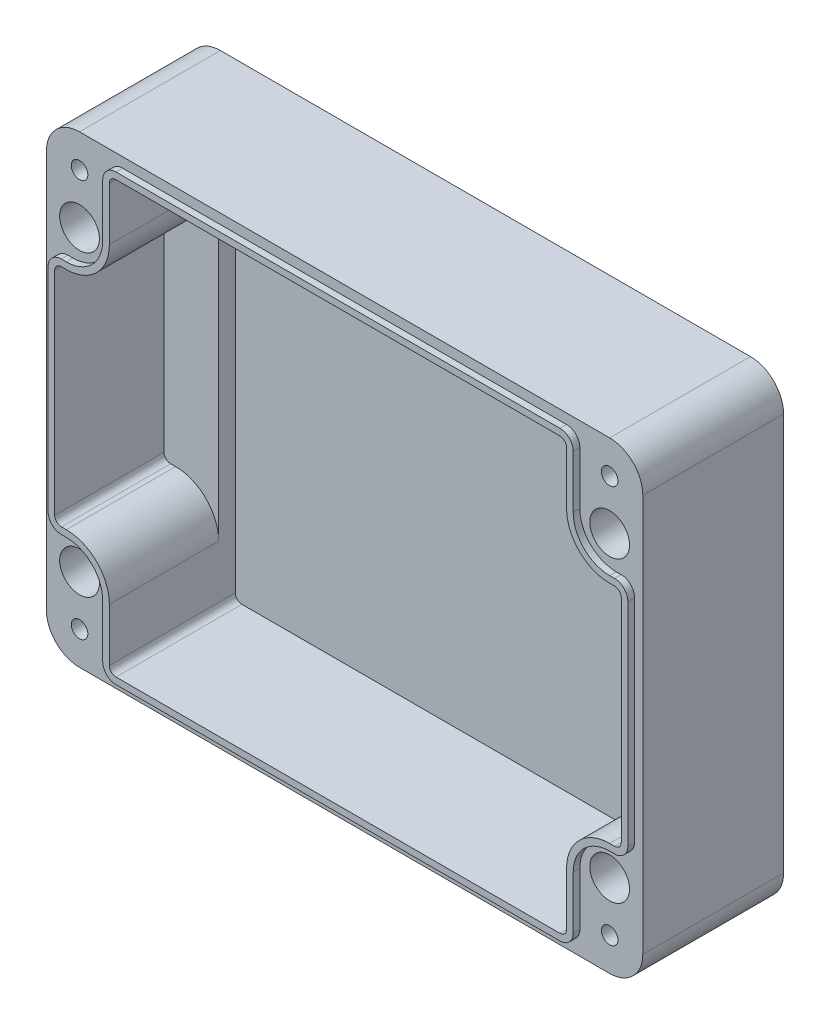
SolidWorks part; units mm, degrees
material "ألمنيوم خلائطي"
ref_plane "Front" through (0, 0, 0) normal (0, 0, 1) x (1, 0, 0)
ref_plane "Top" through (0, 0, 0) normal (0, 1, 0) x (1, 0, 0)
ref_plane "Right" through (0, 0, 0) normal (1, 0, 0) x (0, 0, -1)
sketch "Sketch1" plane through (0, 0, 0) normal (0, 0, 1) x (1, 0, 0)
  line L0 (90, 70) -> (-90, -70) construction
  line L1 (-90, 70) -> (90, 70)
  line L2 (-90, 70) -> (-90, -70)
  line L3 (-90, -70) -> (90, -70)
  line L4 (90, 70) -> (90, -70)
  dimension "D1" = 180
  dimension "D2" = 140
extrude "Boss-Extrude1" add sketch "Sketch1" along normal blind 42.5
sketch "Sketch2" plane through (0, 0, 42.5) normal (0, 0, 1) x (1, 0, 0)
  line L0 (-69, 65) -> (69, -65) construction
  line L1 (-69, 65) -> (69, 65)
  line L2 (-69, 65) -> (-69, 34)
  line L3 (-69, -65) -> (69, -65)
  line L4 (69, 65) -> (69, 34)
  line L5 (-85.5, 34) -> (-69, 34)
  line L6 (-85.5, 34) -> (-85.5, -34)
  line L7 (-85.5, -34) -> (-69, -34)
  line L8 (85.5, 34) -> (85.5, -34)
  line L9 (85.5, 34) -> (-85.5, -34) construction
  line L10 (69, 34) -> (85.5, 34)
  line L11 (69, -34) -> (85.5, -34)
  line L12 (69, -34) -> (69, -65)
  line L13 (-69, -34) -> (-69, -65)
  dimension "D1" = 130
  dimension "D2" = 138
  dimension "D3" = 171
  dimension "D4" = 68
extrude "Cut-Extrude1" cut sketch "Sketch2" against normal blind 36
fillet "Fillet1" radius 2 8 edges at (-69, -65, 24.5) (69, -65, 24.5) (69, 65, 24.5) (-69, 65, 24.5) (85.5, 34, 24.5) (85.5, -34, 24.5) (-85.5, -34, 24.5) (-85.5, 34, 24.5)
fillet "Fillet2" radius 13 4 edges at (69, 34, 24.5) (69, -34, 24.5) (-69, -34, 24.5) (-69, 34, 24.5)
fillet "Fillet3" radius 10 4 edges at (-90, -70, 21.25) (-90, 70, 21.25) (90, 70, 21.25) (90, -70, 21.25)
sketch "Sketch3" plane through (0, 0, 42.5) normal (0, 0, 1) x (1, 0, 0)
  line L12 (-71, 63) -> (-71, 47)
  line L13 (67, 67) -> (-67, 67)
  line L14 (71, 47) -> (71, 63)
  line L15 (83.5, 36) -> (82, 36)
  line L16 (87.5, -32) -> (87.5, 32)
  line L17 (82, -36) -> (83.5, -36)
  line L18 (71, -63) -> (71, -47)
  line L19 (-67, -67) -> (67, -67)
  line L20 (-71, -47) -> (-71, -63)
  line L21 (-83.5, -36) -> (-82, -36)
  line L22 (-87.5, 32) -> (-87.5, -32)
  line L23 (-82, 36) -> (-83.5, 36)
  line L24 (-83.5, -34) -> (-82, -34)
  line L25 (-69, -47) -> (-69, -63)
  line L26 (-67, -65) -> (67, -65)
  line L27 (69, -63) -> (69, -47)
  line L28 (82, -34) -> (83.5, -34)
  line L29 (85.5, -32) -> (85.5, 32)
  line L30 (83.5, 34) -> (82, 34)
  line L31 (69, 47) -> (69, 63)
  line L32 (67, 65) -> (-67, 65)
  line L33 (-69, 63) -> (-69, 47)
  line L34 (-82, 34) -> (-83.5, 34)
  line L35 (-85.5, 32) -> (-85.5, -32)
  line L36 (-83.5, -34) -> (-82, -34)
  line L37 (-69, -47) -> (-69, -63)
  line L38 (-67, -65) -> (67, -65)
  line L39 (69, -63) -> (69, -47)
  line L40 (82, -34) -> (83.5, -34)
  line L41 (85.5, -32) -> (85.5, 32)
  line L42 (83.5, 34) -> (82, 34)
  line L43 (69, 47) -> (69, 63)
  line L44 (67, 65) -> (-67, 65)
  line L45 (-69, 63) -> (-69, 47)
  line L46 (-82, 34) -> (-83.5, 34)
  line L47 (-85.5, 32) -> (-85.5, -32)
  arc A12 (-82, 36) -> (-71, 47) centre (-82, 47) ccw
  arc A13 (-67, 67) -> (-71, 63) centre (-67, 63) ccw
  arc A14 (71, 63) -> (67, 67) centre (67, 63) ccw
  arc A15 (71, 47) -> (82, 36) centre (82, 47) ccw
  arc A16 (87.5, 32) -> (83.5, 36) centre (83.5, 32) ccw
  arc A17 (83.5, -36) -> (87.5, -32) centre (83.5, -32) ccw
  arc A18 (82, -36) -> (71, -47) centre (82, -47) ccw
  arc A19 (67, -67) -> (71, -63) centre (67, -63) ccw
  arc A20 (-71, -63) -> (-67, -67) centre (-67, -63) ccw
  arc A21 (-71, -47) -> (-82, -36) centre (-82, -47) ccw
  arc A22 (-87.5, -32) -> (-83.5, -36) centre (-83.5, -32) ccw
  arc A23 (-83.5, 36) -> (-87.5, 32) centre (-83.5, 32) ccw
  arc A24 (-69, -47) -> (-82, -34) centre (-82, -47) ccw
  arc A25 (-69, -63) -> (-67, -65) centre (-67, -63) ccw
  arc A26 (67, -65) -> (69, -63) centre (67, -63) ccw
  arc A27 (82, -34) -> (69, -47) centre (82, -47) ccw
  arc A28 (83.5, -34) -> (85.5, -32) centre (83.5, -32) ccw
  arc A29 (85.5, 32) -> (83.5, 34) centre (83.5, 32) ccw
  arc A30 (69, 47) -> (82, 34) centre (82, 47) ccw
  arc A31 (69, 63) -> (67, 65) centre (67, 63) ccw
  arc A32 (-67, 65) -> (-69, 63) centre (-67, 63) ccw
  arc A33 (-82, 34) -> (-69, 47) centre (-82, 47) ccw
  arc A34 (-83.5, 34) -> (-85.5, 32) centre (-83.5, 32) ccw
  arc A35 (-85.5, -32) -> (-83.5, -34) centre (-83.5, -32) ccw
  arc A36 (-69, -47) -> (-82, -34) centre (-82, -47) ccw
  arc A37 (-69, -63) -> (-67, -65) centre (-67, -63) ccw
  arc A38 (67, -65) -> (69, -63) centre (67, -63) ccw
  arc A39 (82, -34) -> (69, -47) centre (82, -47) ccw
  arc A40 (83.5, -34) -> (85.5, -32) centre (83.5, -32) ccw
  arc A41 (85.5, 32) -> (83.5, 34) centre (83.5, 32) ccw
  arc A42 (69, 47) -> (82, 34) centre (82, 47) ccw
  arc A43 (69, 63) -> (67, 65) centre (67, 63) ccw
  arc A44 (-67, 65) -> (-69, 63) centre (-67, 63) ccw
  arc A45 (-82, 34) -> (-69, 47) centre (-82, 47) ccw
  arc A46 (-83.5, 34) -> (-85.5, 32) centre (-83.5, 32) ccw
  arc A47 (-85.5, -32) -> (-83.5, -34) centre (-83.5, -32) ccw
  dimension "D1" = 0
  dimension "D2" = 2
extrude "Boss-Extrude2" add sketch "Sketch3" along normal blind 2
hole_wizard "Ø6.5 (6.5) Diameter Hole1" positions "Sketch5" profile "Sketch4" hole size "Ø6.5" standard "ISO" end condition up to next
sketch "Sketch5" plane through (0, 0, 42.5) normal (0, 0, 1) x (1, 0, 0)
  line L0 (-80, 45) -> (80, 45) construction
  line L1 (80, 45) -> (80, -45) construction
  line L2 (80, -45) -> (-80, -45) construction
  line L3 (-80, -45) -> (-80, 45) construction
  line L5 (-80, -45) -> (80, 45) construction
  point P0 (-80, 45)
  point P1 (-80, -45)
  point P3 (80, -45)
  point P5 (80, 45)
  dimension "D1" = 160
  dimension "D2" = 90
sketch "Sketch4" plane through (-80, 45, 42.5) normal (1, 0, 0) x (0, -1, 0)
  line L0 (0, 0) -> (0, 42.5)
  line L1 (0, 42.5) -> (3.25, 42.5)
  line L2 (3.25, 42.5) -> (3.25, 0)
  line L5 (3.25, 0) -> (0, 0)
  line L11 (0, -6.35) -> (0, 107.95) construction
  dimension "Thru Hole Dia." = 6.5
  dimension "Thru Hole Depth" = 42.5
hole_wizard "M5 Tapped Hole1" positions "Sketch7" profile "Sketch6" tap size "M5" standard "ISO"
sketch "Sketch7" plane through (0, 0, 42.5) normal (0, 0, 1) x (1, 0, 0)
  line L0 (-80, 60) -> (80, 60) construction
  line L1 (80, 60) -> (80, -60) construction
  line L2 (80, -60) -> (-80, -60) construction
  line L3 (-80, -60) -> (-80, 60) construction
  line L5 (-80, -60) -> (80, 60) construction
  line L7 (-80, 45) -> (-80, 60) construction
  point P0 (-80, 60)
  point P1 (-80, -60)
  point P3 (80, -60)
  point P5 (80, 60)
  dimension "D1" = 120
sketch "Sketch6" plane through (-80, 60, 42.5) normal (1, 0, 0) x (0, -1, 0)
  line L0 (0, 0) -> (0, 15.2618)
  line L1 (0, 15.2618) -> (2.1, 14)
  line L2 (2.1, 14) -> (2.1, 10)
  line L3 (2.1, 10) -> (2.5, 10)
  line L4 (2.5, 10) -> (2.5, 0)
  line L5 (2.5, 0) -> (0, 0)
  line L10 (0, 15.2618) -> (-2.1, 14) construction
  line L11 (0, -6.35) -> (0, 107.95) construction
  dimension "Tap Drill Dia." = 4.2
  dimension "Tap Drill Depth" = 14
  dimension "Thread Major Dia." = 5
  dimension "Thread Depth" = 10
  dimension "Drill Angle" = 118
sketch "Sketch13" plane through (0, 0, 6.5) normal (0, 0, 1) x (1, 0, 0)
  line L0 (-69, 47) -> (-69, -47)
  line L1 (69, 47) -> (69, -47)
  line L12 (-83.5, -34) -> (-82, -34)
  line L13 (-69, -47) -> (-69, -63)
  line L14 (-67, -65) -> (67, -65)
  line L15 (69, -63) -> (69, -47)
  line L16 (82, -34) -> (83.5, -34)
  line L17 (85.5, -32) -> (85.5, 32)
  line L18 (83.5, 34) -> (82, 34)
  line L19 (69, 47) -> (69, 63)
  line L20 (67, 65) -> (-67, 65)
  line L21 (-69, 63) -> (-69, 47)
  line L22 (-82, 34) -> (-83.5, 34)
  line L23 (-85.5, 32) -> (-85.5, -32)
  line L24 (-83.5, -34) -> (-82, -34)
  line L28 (82, -34) -> (83.5, -34)
  line L29 (85.5, -32) -> (85.5, 32)
  line L30 (83.5, 34) -> (82, 34)
  line L34 (-82, 34) -> (-83.5, 34)
  line L35 (-85.5, 32) -> (-85.5, -32)
  arc A12 (-69, -47) -> (-82, -34) centre (-82, -47) ccw
  arc A13 (-69, -63) -> (-67, -65) centre (-67, -63) ccw
  arc A14 (67, -65) -> (69, -63) centre (67, -63) ccw
  arc A15 (82, -34) -> (69, -47) centre (82, -47) ccw
  arc A16 (83.5, -34) -> (85.5, -32) centre (83.5, -32) ccw
  arc A17 (85.5, 32) -> (83.5, 34) centre (83.5, 32) ccw
  arc A18 (69, 47) -> (82, 34) centre (82, 47) ccw
  arc A19 (69, 63) -> (67, 65) centre (67, 63) ccw
  arc A20 (-67, 65) -> (-69, 63) centre (-67, 63) ccw
  arc A21 (-82, 34) -> (-69, 47) centre (-82, 47) ccw
  arc A22 (-83.5, 34) -> (-85.5, 32) centre (-83.5, 32) ccw
  arc A23 (-85.5, -32) -> (-83.5, -34) centre (-83.5, -32) ccw
  arc A24 (-69, -47) -> (-82, -34) centre (-82, -47) ccw
  arc A27 (82, -34) -> (69, -47) centre (82, -47) ccw
  arc A28 (83.5, -34) -> (85.5, -32) centre (83.5, -32) ccw
  arc A29 (85.5, 32) -> (83.5, 34) centre (83.5, 32) ccw
  arc A30 (69, 47) -> (82, 34) centre (82, 47) ccw
  arc A33 (-82, 34) -> (-69, 47) centre (-82, 47) ccw
  arc A34 (-83.5, 34) -> (-85.5, 32) centre (-83.5, 32) ccw
  arc A35 (-85.5, -32) -> (-83.5, -34) centre (-83.5, -32) ccw
  dimension "D1" = 0
extrude "Boss-Extrude3" add sketch "Sketch13" along normal blind 5
hole_wizard "M3 Tapped Hole1" [suppressed] positions "Sketch12" profile "Sketch11" tap size "M3" standard "ISO"
sketch "Sketch12" plane through (-145.9309, 104.9926, 11.5) normal (0, 0, 1) x (1, 0, 0)
  line L0 (223.4309, -84.9926) -> (68.4309, -84.9926) construction
  line L1 (68.4309, -84.9926) -> (68.4309, -124.9926) construction
  line L2 (68.4309, -124.9926) -> (223.4309, -124.9926) construction
  line L3 (223.4309, -124.9926) -> (223.4309, -84.9926) construction
  line L4 (223.4309, -84.9926) -> (68.4309, -124.9926) construction
  line L6 (145.9309, -124.9926) -> (145.9309, -169.9926) construction
  line L7 (78.9309, -169.9926) -> (212.9309, -169.9926) construction
  point P0 (223.4309, -84.9926)
  point P1 (68.4309, -84.9926)
  point P3 (68.4309, -124.9926)
  point P5 (223.4309, -124.9926)
  dimension "D1" = 155
  dimension "D2" = 40
sketch "Sketch11" plane through (77.5, 20, 11.5) normal (1, 0, 0) x (0, -1, 0)
  line L0 (0, 0) -> (0, 9.2511)
  line L1 (0, 9.2511) -> (1.25, 8.5)
  line L2 (1.25, 8.5) -> (1.25, 0)
  line L5 (1.25, 0) -> (0, 0)
  line L10 (0, 9.2511) -> (-1.25, 8.5) construction
  line L11 (0, -6.35) -> (0, 107.95) construction
  dimension "Tap Drill Dia." = 2.5
  dimension "Tap Drill Depth" = 8.5
  dimension "Drill Angle" = 118
cosmetic thread "Hole Thread1" [suppressed] parameters "D1"=6, "D2"=3
cosmetic thread "Hole Thread2" [suppressed] parameters "D1"=6, "D2"=3
cosmetic thread "Hole Thread3" [suppressed] parameters "D1"=6, "D2"=3
cosmetic thread "Hole Thread4" [suppressed] parameters "D1"=6, "D2"=3
sketch "Sketch18" plane through (0, 0, 42.5) normal (0, 0, 1) x (1, 0, 0)
  circle A0 centre (-80, 45) radius 6
  circle A1 centre (-80, -45) radius 6
  circle A2 centre (80, -45) radius 6
  circle A3 centre (80, 45) radius 6
  dimension "D1" = 12
extrude "Cut-Extrude4" cut sketch "Sketch18" against normal offset from surface (32.5 mm away) 10 up to face at (-76.75, 45, 0)
sketch "Sketch19" [suppressed] plane through (0, 0, 42.5) normal (0, 0, 1) x (1, 0, 0)
  line L4 (-90, 60) -> (-90, -60)
  line L5 (-80, -70) -> (80, -70)
  line L6 (90, -60) -> (90, 60)
  line L7 (80, 70) -> (-80, 70)
  line L8 (-90, 60) -> (-90, -60)
  line L9 (-80, -70) -> (80, -70)
  line L10 (90, -60) -> (90, 60)
  line L11 (80, 70) -> (-80, 70)
  arc A4 (-90, -60) -> (-80, -70) centre (-80, -60) ccw
  arc A5 (80, -70) -> (90, -60) centre (80, -60) ccw
  arc A6 (90, 60) -> (80, 70) centre (80, 60) ccw
  arc A7 (-80, 70) -> (-90, 60) centre (-80, 60) ccw
  arc A8 (-90, -60) -> (-80, -70) centre (-80, -60) ccw
  arc A9 (80, -70) -> (90, -60) centre (80, -60) ccw
  arc A10 (90, 60) -> (80, 70) centre (80, 60) ccw
  arc A11 (-80, 70) -> (-90, 60) centre (-80, 60) ccw
  dimension "D1" = 0
extrude "Boss-Extrude4" [suppressed] add sketch "Sketch19" along normal blind 20
